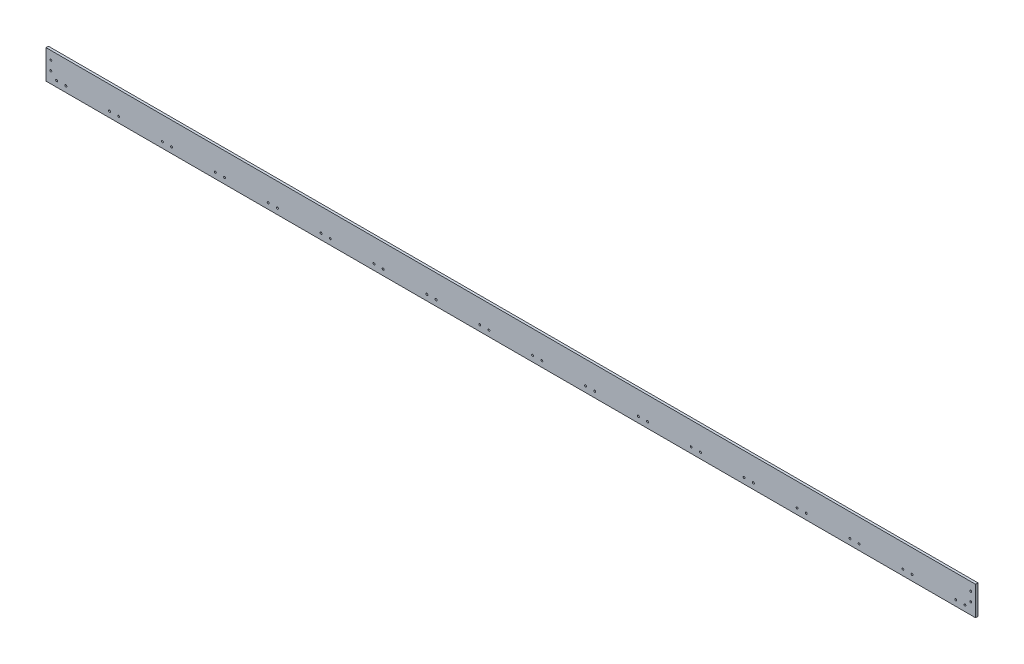
SolidWorks part; units mm, degrees
ref_plane "Front Plane" through (0, 0, 0) normal (0, 0, 1) x (1, 0, 0)
ref_plane "Top Plane" through (0, 0, 0) normal (0, 1, 0) x (1, 0, 0)
ref_plane "Right Plane" through (0, 0, 0) normal (1, 0, 0) x (0, 0, -1)
sketch "Sketch1" plane through (0, 0, 0) normal (0, 0, 1) x (1, 0, 0)
  line L1 (0, 0) -> (2438.4, 0)
  line L2 (0, 0) -> (0, 76.2)
  line L3 (0, 76.2) -> (2438.4, 76.2)
  line L4 (2438.4, 0) -> (2438.4, 76.2)
  dimension "D1" = 76.2
  dimension "D2" = 2438.4
extrude "Boss-Extrude1" add sketch "Sketch1" along normal blind 6.35
sketch "Sketch2" plane through (0, 0, 6.35) normal (0, 0, 1) x (1, 0, 0)
  line L0 (27.94, 0) -> (27.94, 12.7) construction
  line L2 (0, 15.24) -> (25.4, 15.24) construction
  line L3 (0, 76.2) -> (0, 0) construction
  line L4 (0, 0) -> (2438.4, 0) construction
  line L5 (30.48, 15.24) -> (49.53, 15.24) construction
  circle A0 centre (27.94, 15.24) radius 2.54
  circle A1 centre (52.07, 15.24) radius 2.54
  point P13 (1219.2, 76.2)
  dimension "D2" = 5.08
  dimension "D1" = 5.08
  dimension "D3" = 19.05
  dimension "D5" = 12.7
  dimension "D4" = 25.4
extrude "Cut-Extrude1" cut sketch "Sketch2" against normal up to surface (6.35 mm away) contours A1 | A0 up to face at (1219.2, 38.1, 0)
sketch "Sketch3" plane through (0, 0, 6.35) normal (0, 0, 1) x (1, 0, 0)
  line L0 (0, 76.2) -> (0, 0) construction
  line L1 (2438.4, 76.2) -> (0, 76.2) construction
  line L2 (12.7, 41.91) -> (0, 41.91) construction
  line L3 (12.7, 51.435) -> (12.7, 32.385) construction
  line L4 (0, 41.91) -> (0, 38.1) construction
  line L5 (1219.2, 76.2) -> (1219.2, 0) construction
  line L6 (0, 0) -> (2438.4, 0) construction
  circle A0 centre (12.7, 29.845) radius 2.54
  circle A1 centre (12.7, 53.975) radius 2.54
  circle A2 centre (2425.7, 29.845) radius 2.54
  circle A3 centre (2425.7, 53.975) radius 2.54
  point P13 (0, 38.1)
  point P15 (1219.2, 76.2)
  point P17 (12.7, 41.91)
  point P27 (12.7, 41.91)
  dimension "D2" = 5.08
  dimension "D1" = 5.08
  dimension "D3" = 19.05
  dimension "D4" = 12.7
  dimension "D5" = 3.81
extrude "Cut-Extrude2" cut sketch "Sketch3" against normal up to surface (6.35 mm away) up to face at (25.4, 15.24, 0)
pattern_linear "LPattern2" count 18 spacing 138.7288 along (1, 0, 0) of "Cut-Extrude1"
equation "\"vertical-component-width\"= 96in"
equation "\"vertical-component-height\"= 3in"
equation "\"material-thickness\"= .25in"
equation "\"D1@Sketch1\"=\"vertical-component-height\""
equation "\"D2@Sketch1\"=\"vertical-component-width\""
equation "\"D1@Boss-Extrude1\"=\"material-thickness\""
equation "\"mounting-hole-diameter\"= .2"
equation "\"mounting-hole-pair-left-to-mount-edge-left\"= 1in"
equation "\"mounting-hole-bottom-to-mount-edge-bottom\"= .5in"
equation "\"mounting-hole-pair-distance-between-holes\"= .75in"
equation "\"distance-between-mounting-hole-pairs\"= ( \"vertical-component-width\" - 2 * \"mounting-hole-pair-left-to-mount-edge-left\" - \"num-mounting-hole-pairs\" * ( 2 * \"mounting-hole-diameter\" + \"mounting-hole-pair-distance-between-holes\" ) ) / ( \"num-mounting-hole-pairs\" - 1 )"
equation "\"num-mounting-hole-pairs\"=18"
equation "\"D3@Sketch2\"=\"mounting-hole-pair-distance-between-holes\""
equation "\"D5@Sketch2\"=\"mounting-hole-bottom-to-mount-edge-bottom\""
equation "\"D4@Sketch2\"=\"mounting-hole-pair-left-to-mount-edge-left\""
equation "\"D3@LPattern2\"=\"mounting-hole-pair-left-to-next-mounting-hole-pair-left\""
equation "\"D2@Sketch2\"=\"mounting-hole-diameter\""
equation "\"D1@Sketch2\"=\"mounting-hole-diameter\""
equation "\"mounting-hole-pair-left-to-next-mounting-hole-pair-left\"= \"distance-between-mounting-hole-pairs\" + 2 * \"mounting-hole-diameter\" + \"mounting-hole-pair-distance-between-holes\""
equation "\"edge-mounting-hole-pair-inset\"=0.5"
equation "\"D4@Sketch3\"=\"edge-mounting-hole-pair-inset\""
equation "\"edge-mounting-hole-pair-offset-from-mount-vertical-center\"= 0.15"
equation "\"D5@Sketch3\"=\"edge-mounting-hole-pair-offset-from-mount-vertical-center\""
equation "\"D3@Sketch3\"=\"mounting-hole-pair-distance-between-holes\""
